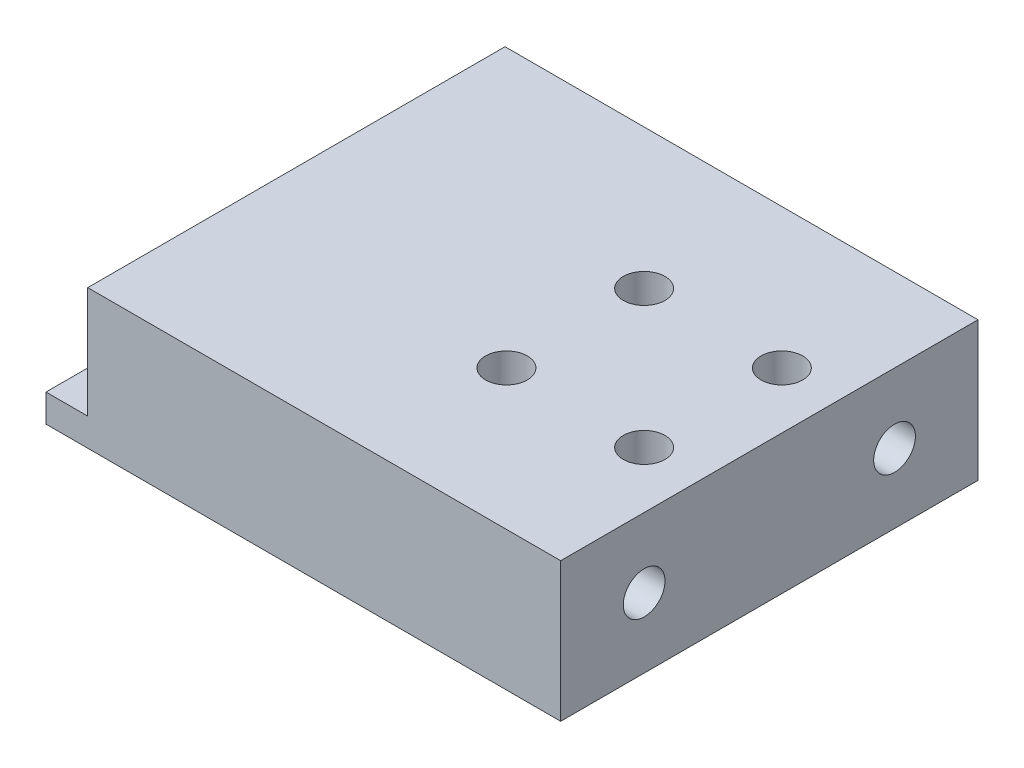
SolidWorks part; units mm, degrees
ref_plane "Спереди" through (0, 0, 0) normal (0, 0, 1) x (1, 0, 0)
ref_plane "Сверху" through (0, 0, 0) normal (0, 1, 0) x (1, 0, 0)
ref_plane "Справа" through (0, 0, 0) normal (1, 0, 0) x (0, 0, -1)
sketch "Эскиз1" plane through (0, 0, 0) normal (0, 1, 0) x (1, 0, 0)
  line L0 (28, 15) -> (21.9896, 21.0104) construction
  line L1 (0, 0) -> (37, 0)
  line L2 (0, 0) -> (0, 30)
  line L3 (0, 30) -> (37, 30)
  line L4 (37, 0) -> (37, 30)
  line L5 (28, 15) -> (28, 25.5625) construction
  line L6 (28, 15) -> (34.0104, 21.0104) construction
  line L7 (28, 15) -> (34.0104, 8.9896) construction
  line L8 (28, 15) -> (21.9896, 8.9896) construction
  circle A0 centre (28, 15) radius 7 construction
  circle A1 centre (28, 15) radius 8.5 construction
  circle A2 centre (32.9497, 19.9497) radius 1.5
  circle A3 centre (23.0503, 19.9497) radius 1.5
  circle A4 centre (32.9497, 10.0503) radius 1.5
  circle A5 centre (23.0503, 10.0503) radius 1.5
  dimension "D3" = 15
  dimension "D5" = 14
  dimension "D6" = 17
  dimension "D1" = 37
  dimension "D2" = 30
  dimension "D4" = 9
  dimension "D7" = 45
extrude "Бобышка-Вытянуть1" add sketch "Эскиз1" along normal blind 10
sketch "Эскиз2" plane through (37, 0, 0) normal (1, 0, 0) x (0, 0, -1)
  line L0 (0, 5) -> (30, 5) construction
  line L1 (0, 10) -> (0, 0) construction
  line L2 (30, 10) -> (30, 0) construction
  circle A0 centre (6, 5) radius 1.5
  circle A1 centre (24, 5) radius 1.5
  dimension "D1" = 3
  dimension "D2" = 3
  dimension "D3" = 6
  dimension "D4" = 18
extrude "Вырез-Вытянуть1" cut sketch "Эскиз2" against normal blind 6
sketch "Эскиз3" plane through (0, 0, 0) normal (-1, 0, 0) x (0, 0, 1)
  line L0 (-30, 10) -> (0, 10) construction
  line L1 (-30, 10) -> (0, 10)
  line L2 (-30, 10) -> (-30, 2)
  line L3 (-30, 2) -> (0, 2)
  line L4 (0, 10) -> (0, 2)
  line L5 (-30, 0) -> (0, 0) construction
  point P6 (-15, 10)
  point P9 (-15, 0)
  dimension "D1" = 8
  dimension "D2" = 30
extrude "Вырез-Вытянуть2" cut sketch "Эскиз3" against normal blind 3
sketch "Эскиз4" plane through (0, 0, 0) normal (-1, 0, 0) x (0, 0, 1)
  line L0 (-20, 5.4) -> (-9, 5.4) construction
  line L1 (0, 10) -> (-30, 10) construction
  line L2 (-20, 4.4) -> (-10, 4.4) construction
  circle A0 centre (-20, 5.4) radius 1
  circle A1 centre (-10, 5.4) radius 1
  point P5 (-15, 10)
  dimension "D1" = 5
  dimension "D2" = 2
  dimension "D3" = 10
  dimension "D4" = 4.6
extrude "Вырез-Вытянуть3" cut sketch "Эскиз4" against normal blind 7
